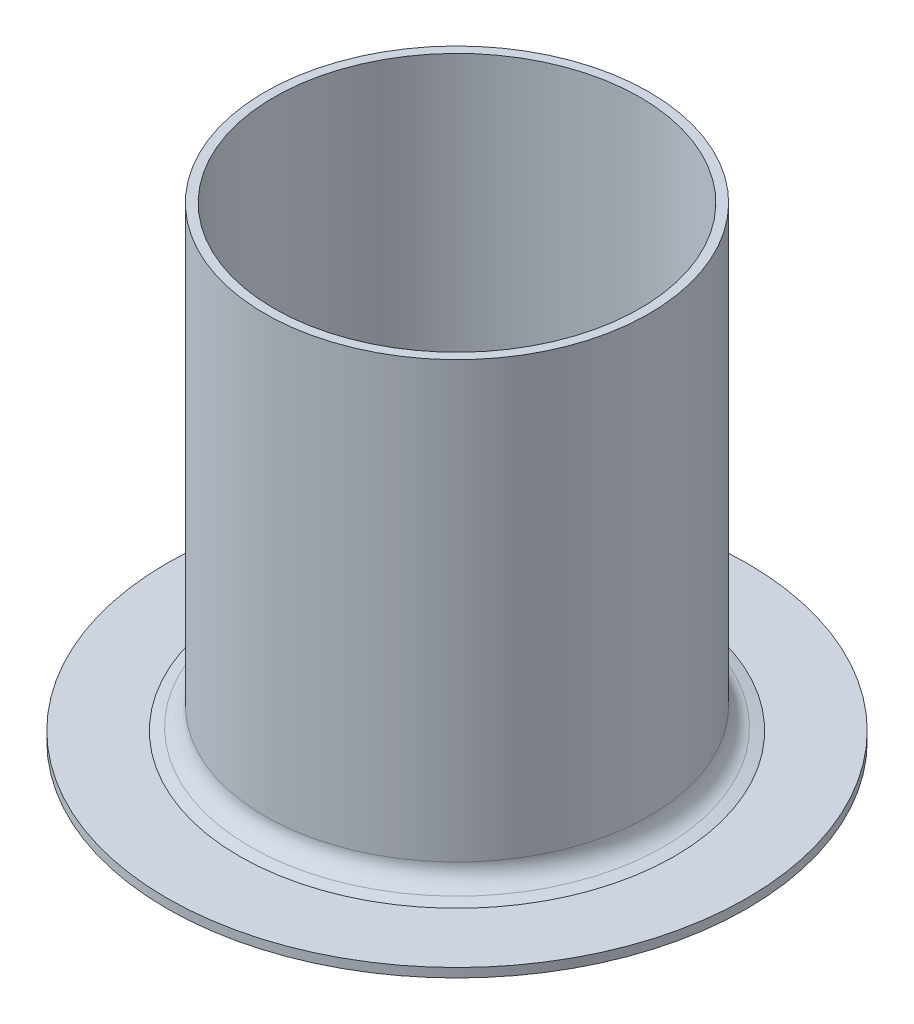
SolidWorks part; units mm, degrees
ref_plane "Front Plane" through (0, 0, 0) normal (0, 0, 1) x (1, 0, 0)
ref_plane "Top Plane" through (0, 0, 0) normal (0, 1, 0) x (1, 0, 0)
ref_plane "Right Plane" through (0, 0, 0) normal (1, 0, 0) x (0, 0, -1)
sketch "Sketch2" plane through (0, 0, 0) normal (0, 0, 1) x (1, 0, 0)
  line L0 (0, 0) -> (38.1, 0) construction
  line L2 (38.1, 0) -> (50.8, 0)
  line L4 (38.1, 1.5875) -> (50.8, 1.5875)
  line L5 (50.8, 0) -> (50.8, 1.5875)
  line L7 (33.6423, 5.4473) -> (33.6423, 81.6473)
  line L8 (33.6423, 81.6473) -> (32.0548, 81.6473)
  line L9 (32.0548, 5.5178) -> (32.0548, 81.6473)
  line L21 (0, 0) -> (0, 48.0954) construction
  line L22 (38.1, 0) -> (35.82, 0.6109)
  line L23 (38.1, 1.5875) -> (36.2169, 2.0921)
  line L24 (38.1, 0) -> (38.1, 1.5875) construction
  line L25 (33.6423, 5.4473) -> (32.0548, 5.5178) construction
  line L26 (35.82, 0.6109) -> (36.2169, 2.0921) construction
  arc A0 (35.82, 0.6109) -> (32.0548, 5.5178) centre (37.1348, 5.5178) cw
  arc A1 (36.2169, 2.0921) -> (33.6423, 5.4473) centre (37.1159, 5.4473) cw
  dimension "D2" = 5.08
  dimension "D1" = 38.1
  dimension "D3" = 1.5875
  dimension "D4" = 1.5875
  dimension "D5" = 15
  dimension "D6" = 76.2
  dimension "D7" = 50.8
  dimension "D8" = 32.0548
revolve "Revolve1" add sketch "Sketch2" angle 360 about L21
